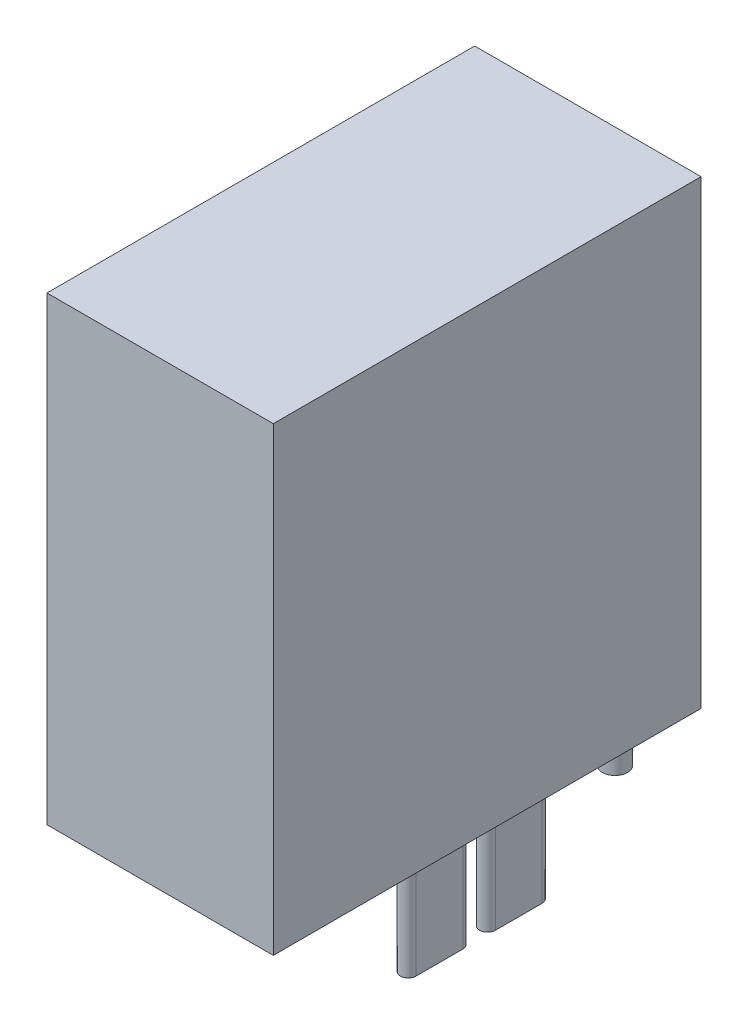
SolidWorks part; units mm, degrees
material "ABS"
ref_plane "Plan de face" through (0, 0, 0) normal (0, 0, 1) x (1, 0, 0)
ref_plane "Plan de dessus" through (0, 0, 0) normal (0, 1, 0) x (1, 0, 0)
ref_plane "Plan de droite" through (0, 0, 0) normal (1, 0, 0) x (0, 0, -1)
sketch "Esquisse1" plane through (0, 0, 0) normal (0, 0, 1) x (1, 0, 0)
  line L1 (0, 0) -> (7.25, 0)
  line L2 (0, 0) -> (0, 14.75)
  line L3 (0, 14.75) -> (7.25, 14.75)
  line L4 (7.25, 0) -> (7.25, 14.75)
  dimension "D1" = 14.75
  dimension "D2" = 7.25
extrude "Extrusion1" add sketch "Esquisse1" along normal blind 13.7
sketch "Esquisse2" plane through (0, 0, 0) normal (0, -1, 0) x (1, 0, 0)
  line L0 (9.4083, 7.59) -> (-2.3124, 7.59) construction
  line L1 (0, 13.7) -> (7.25, 13.7) construction
  line L2 (3.35, -2.5227) -> (3.35, 15.0397) construction
  line L3 (0, 13.7) -> (0, 0) construction
  line L4 (6.21, 5.5214) -> (6.21, 9.2581) construction
  line L6 (0.79, 5.3038) -> (0.79, 9.2581) construction
  line L7 (1.04, 6.84) -> (1.04, 8.34)
  line L8 (0.54, 6.84) -> (0.54, 8.34)
  line L9 (6.46, 6.84) -> (6.46, 8.34)
  line L10 (0.79, 5.5214) -> (0.79, 9.2581) construction
  line L11 (5.96, 6.84) -> (5.96, 8.34)
  line L12 (3.9883, 7.59) -> (-7.7324, 7.59) construction
  line L13 (1.04, 4.3) -> (1.04, 5.8)
  line L14 (0.79, 2.9814) -> (0.79, 6.7181) construction
  line L15 (3.9883, 5.05) -> (-7.7324, 5.05) construction
  line L16 (6.21, 2.9814) -> (6.21, 6.7181) construction
  line L17 (3.35, -5.0627) -> (3.35, 12.4997) construction
  line L18 (5.96, 4.3) -> (5.96, 5.8)
  line L19 (0.54, 4.3) -> (0.54, 5.8)
  line L20 (6.46, 4.3) -> (6.46, 5.8)
  line L21 (0.79, 2.7638) -> (0.79, 6.7181) construction
  line L22 (9.4083, 5.05) -> (-2.3124, 5.05) construction
  arc A0 (5.96, 6.84) -> (6.46, 6.84) centre (6.21, 6.84) ccw
  arc A1 (5.96, 8.34) -> (6.46, 8.34) centre (6.21, 8.34) cw
  arc A2 (0.54, 6.84) -> (1.04, 6.84) centre (0.79, 6.84) ccw
  arc A3 (0.54, 8.34) -> (1.04, 8.34) centre (0.79, 8.34) cw
  arc A4 (0.54, 5.8) -> (1.04, 5.8) centre (0.79, 5.8) cw
  arc A5 (0.54, 4.3) -> (1.04, 4.3) centre (0.79, 4.3) ccw
  arc A6 (5.96, 5.8) -> (6.46, 5.8) centre (6.21, 5.8) cw
  arc A7 (5.96, 4.3) -> (6.46, 4.3) centre (6.21, 4.3) ccw
  dimension "D1" = 6.11
  dimension "D2" = 3.35
  dimension "D3" = 2.86
  dimension "D4" = 2.56
  dimension "D7" = 0.25
  dimension "D8" = 0.25
extrude "Extrusion2" add sketch "Esquisse2" along normal blind 3.65
sketch "Esquisse3" plane through (0, 0, 0) normal (0, -1, 0) x (1, 0, 0)
  line L0 (8.2403, 8.5269) -> (-1.0564, 8.5269) construction
  line L1 (8.2403, 0.9569) -> (-1.2106, 0.9569) construction
  line L2 (3.35, -1.0258) -> (3.35, 14.6377) construction
  line L3 (0, 13.7) -> (0, 0) construction
  line L4 (4.05, -0.2988) -> (4.05, 2.2127) construction
  circle A0 centre (4.05, 0.9569) radius 0.4
  circle A1 centre (2.65, 0.9569) radius 0.4
  circle A2 centre (1.25, 0.9569) radius 0.4
  circle A3 centre (5.45, 0.9569) radius 0.4
  dimension "D1" = 7.57
  dimension "D2" = 3.35
  dimension "D3" = 0.7
extrude "Extrusion3" add sketch "Esquisse3" along normal blind 2
